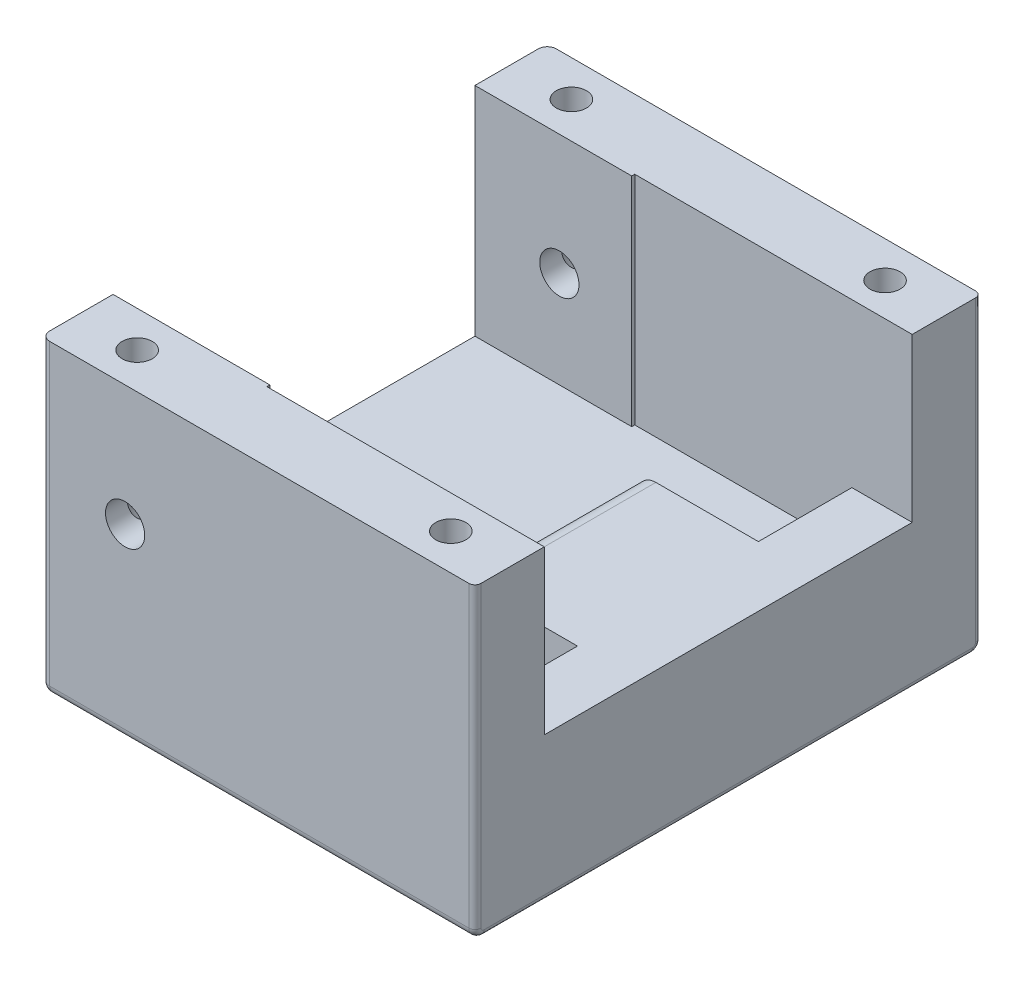
SolidWorks part; units mm, degrees
ref_plane "Ebene vorne" through (0, 0, 0) normal (0, 0, 1) x (1, 0, 0)
ref_plane "Ebene oben" through (0, 0, 0) normal (0, 1, 0) x (1, 0, 0)
ref_plane "Ebene rechts" through (0, 0, 0) normal (1, 0, 0) x (0, 0, -1)
sketch "Sketch1" plane through (0, 0, 0) normal (0, 1, 0) x (1, 0, 0)
  line L1 (18, -15) -> (-18, -15)
  line L2 (18, -15) -> (18, 15)
  line L3 (18, 15) -> (-18, 15)
  line L4 (-18, -15) -> (-18, 15)
  line L5 (18, -15) -> (-18, 15) construction
  line L6 (18, 15) -> (-18, -15) construction
  point P0 (0, 0)
  dimension "D1" = 30
  dimension "D2" = 36
extrude "Base Plate" add sketch "Sketch1" along normal blind 7.5
sketch "Sketch2" plane through (0, 0, 0) normal (0, -1, 0) x (1, 0, 0)
  line L0 (-18, -21) -> (-18, -15)
  line L1 (18, 15) -> (-18, 15)
  line L2 (18, 15) -> (18, 21)
  line L3 (18, 21) -> (-18, 21)
  line L4 (-18, 15) -> (-18, 21)
  line L5 (18, -15) -> (-18, -15)
  line L6 (18, -15) -> (18, -21)
  line L7 (18, -21) -> (-18, -21)
  dimension "D1" = 6
  dimension "D2" = 6
  dimension "D3" = 36
extrude "Side Walls" add sketch "Sketch2" against normal offset from surface (25.5 mm away) 18 up to face at (0, 7.5, 0) offset beyond the face yes
sketch "Sketch4" plane through (0, 25.5, 0) normal (0, 1, 0) x (1, 0, 0)
  line L0 (-18, 15) -> (-18, 21) construction
  line L1 (0, 0) -> (-11.3326, 0) construction
  line L2 (18, -15) -> (18, -21) construction
  line L5 (18, 18) -> (-16.1906, 18) construction
  line L6 (18, 21) -> (18, 15) construction
  line L7 (18, -18) -> (-12.0772, -18) construction
  line L8 (18, -15) -> (18, -21) construction
  circle A0 centre (-13, -18) radius 1.25
  circle A1 centre (13, -18) radius 1.25
  circle A2 centre (13, 18) radius 1.25
  circle A3 centre (-13, 18) radius 1.25
  dimension "D1" = 2.5
  dimension "D2" = 5
  dimension "D5" = 5
extrude "M2 Screws" cut sketch "Sketch4" against normal up to surface (25.5 mm away) up to face at (0, 0, 0)
sketch "Sketch5" plane through (0, 0, -15) normal (0, 0, 1) x (1, 0, 0)
  line L1 (18, 7.5) -> (-18, 7.5) construction
  line L2 (-18, 25.5) -> (-18, 7.5) construction
  circle A0 centre (-11, 15.5) radius 1.625
  dimension "D1" = 3.25
  dimension "D2" = 7
  dimension "D3" = 8
sketch "Sketch6" plane through (0, 7.5, 0) normal (0, 1, 0) x (1, 0, 0)
  line L0 (18, -15) -> (18, 15) construction
  line L1 (13, 15) -> (18, 15)
  line L2 (13, 15) -> (13, -15)
  line L3 (13, -15) -> (18, -15)
  line L4 (18, 15) -> (18, -15)
  line L5 (13, 15) -> (18, -15) construction
  line L6 (13, -15) -> (18, 15) construction
  line L7 (-15, 0) -> (2.1882, 0) construction
  line L9 (-18, -15) -> (18, -15) construction
  point P0 (15.5, 0)
  dimension "D1" = 5
extrude "Return Stopper" add sketch "Sketch6" along normal offset from surface (4.5 mm away) 4.5 up to face at (0, 7.5, 0) offset beyond the face yes
sketch "Sketch9" plane through (0, 7.5, 0) normal (0, 1, 0) x (1, 0, 0)
  line L0 (13, 15) -> (13, -15) construction
  line L1 (13, -7.5) -> (3, -7.5)
  line L2 (13, -7.5) -> (13, 7.5)
  line L3 (13, 7.5) -> (3, 7.5)
  line L4 (3, -7.5) -> (3, 7.5)
  line L5 (13.4797, 0) -> (4.6476, 0) construction
  line L6 (13, 0) -> (7.6237, 0) construction
  dimension "D1" = 10
  dimension "D2" = 15
extrude "Boss-Extrude1" add sketch "Sketch9" along normal up to surface (4.5 mm away) up to face at (15.5, 12, 0)
sketch "Sketch7" plane through (0, 0, 0) normal (0, 1, 0) x (-1, 0, 0)
  line L0 (0, 0) -> (11.2549, 0) construction
  line L1 (-18, 21) -> (-18, -21) construction
  circle A0 centre (-11, 0) radius 6.25
  dimension "D1" = 12.5
  dimension "D2" = 7
extrude "Magnet Pocket" cut sketch "Sketch7" along normal offset from surface (11 mm away) 1 up to face at (11.75, 12, 0)
sketch "Sketch8" plane through (0, 0, 0) normal (0, -1, 0) x (1, 0, 0)
  circle A0 centre (13, -18) radius 2
  circle A1 centre (-13, -18) radius 2
  circle A2 centre (13, 18) radius 2
  circle A3 centre (-13, 18) radius 2
  dimension "D1" = 4
extrude "M2 Screw Head" cut sketch "Sketch8" against normal blind 1.5
extrude "M3 Achse" cut sketch "Sketch5" against normal through all both and the other way through all
fillet "Fillet1" radius 1.5 1 edges at (3, 12, 0)
sketch "Sketch11" plane through (0, 0, -15) normal (0, 0, 1) x (1, 0, 0)
  line L0 (18, 25.5) -> (-18, 25.5) construction
  line L1 (18, 12) -> (-5, 12)
  line L2 (18, 12) -> (18, 25.5)
  line L3 (18, 25.5) -> (-5, 25.5)
  line L4 (-5, 12) -> (-5, 25.5)
  circle A0 centre (-11, 15.5) radius 1.625 construction
  dimension "D1" = 6
extrude "Leaver Space" cut sketch "Sketch11" against normal blind 0.25 and the other way offset from surface (30.25 mm away) 0.25
sketch "Sketch12" plane through (0, 0, -15) normal (0, 0, 1) x (1, 0, 0)
  line L0 (13, 12) -> (-5, 12) construction
  line L1 (13, 7.5) -> (-5, 7.5)
  line L2 (13, 7.5) -> (13, 12)
  line L3 (13, 12) -> (-5, 12)
  line L4 (-5, 7.5) -> (-5, 12)
  line L5 (-5, 12) -> (-5, 25.5) construction
extrude "More Space left" cut sketch "Sketch12" against normal up to surface (0.25 mm away) up to face at (6.5, 18.75, -15.25)
sketch "Sketch13" plane through (0, 0, 15) normal (0, 0, -1) x (-1, 0, 0)
  line L1 (-13, 7.5) -> (5, 7.5)
  line L2 (-13, 7.5) -> (-13, 12)
  line L3 (-13, 12) -> (5, 12)
  line L4 (5, 7.5) -> (5, 12)
extrude "More Space right" cut sketch "Sketch13" against normal up to surface (0.25 mm away) up to face at (6.5, 18.75, 15.25)
fillet "Fillet2" radius 0.75 1 edges at (0, 0, -21)
fillet "Fillet3" radius 0.75 1 edges at (0, 0, 21)
fillet "Fillet4" radius 0.75 5 edges at (-18, 13.125, 21) (-18, 0, 0) (-18, 0.2197, -20.7803) (-18, 0.2197, 20.7803) (-18, 13.125, -21)
fillet "Fillet5" radius 0.5 5 edges at (18, 13.125, 21) (18, 0.2197, -20.7803) (18, 0, 0) (18, 0.2197, 20.7803) (18, 13.125, -21)
